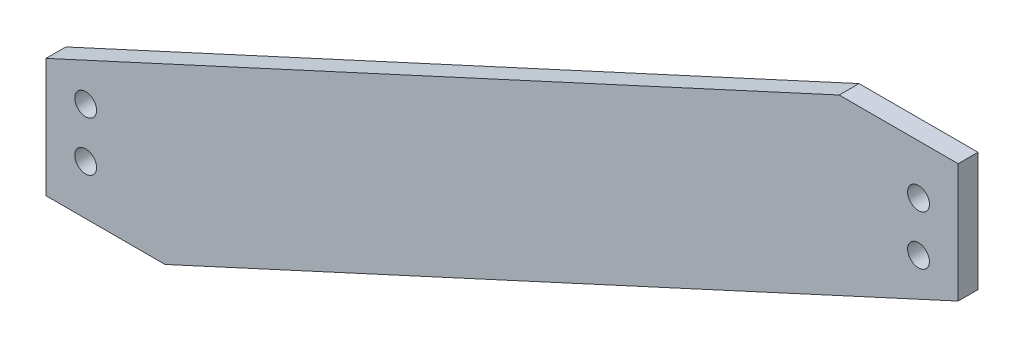
SolidWorks part; units mm, degrees
ref_plane "Front" through (0, 0, 0) normal (0, 0, 1) x (1, 0, 0)
ref_plane "Top" through (0, 0, 0) normal (0, 1, 0) x (1, 0, 0)
ref_plane "Right" through (0, 0, 0) normal (1, 0, 0) x (0, 0, -1)
sketch "Sketch1" plane through (0, 0, 0) normal (0, 0, 1) x (1, 0, 0)
  line L0 (0, 0) -> (20, 0)
  line L1 (20, 0) -> (230, 122)
  line L2 (230, 122) -> (210, 122)
  line L3 (210, 122) -> (0, 0)
  dimension "D1" = 20
  dimension "D2" = 122
  dimension "D3" = 230
extrude "Boss-Extrude1" add sketch "Sketch1" along normal blind 5
sketch "Sketch2" plane through (0, 0, 5) normal (0, 0, 1) x (1, 0, 0)
  line L0 (0, 0) -> (0, 30)
  line L1 (0, 30) -> (200, 122)
  line L2 (200, 122) -> (210, 122)
  line L3 (210, 122) -> (230, 122)
  line L4 (230, 122) -> (230, 92)
  line L5 (230, 92) -> (30, 0)
  line L6 (30, 0) -> (0, 0)
  dimension "D1" = 30
  dimension "D2" = 30
  dimension "D3" = 30
extrude "Boss-Extrude2" add sketch "Sketch2" against normal up to surface (5 mm away) up to face at (115, 61, 0)
hole_wizard "M5 Clearance Hole1" positions "Sketch3" profile "Sketch4" hole size "M5" standard "ISO" end condition through all
sketch "Sketch3" plane through (0, 0, 5) normal (0, 0, 1) x (1, 0, 0)
  line L0 (0, 30) -> (0, 0) construction
  line L1 (0, 0) -> (30, 0) construction
  line L2 (230, 92) -> (230, 122) construction
  line L3 (230, 122) -> (200, 122) construction
  line L4 (10, 25) -> (10, 0) construction
  line L6 (220, 97) -> (220, 122) construction
  point P0 (10, 25)
  point P2 (220, 97)
  point P22 (10, 12.5)
  point P24 (220, 109.5)
  dimension "D1" = 10
  dimension "D2" = 25
  dimension "D3" = 10
  dimension "D4" = 25
sketch "Sketch4" plane through (10, 25, 5) normal (1, 0, 0) x (0, -1, 0)
  line L0 (0, 0) -> (0, 5)
  line L1 (0, 5) -> (2.75, 5)
  line L2 (2.75, 5) -> (2.75, 0)
  line L5 (2.75, 0) -> (0, 0)
  line L11 (0, -6.35) -> (0, 107.95) construction
  dimension "Thru Hole Dia." = 5.5
  dimension "Thru Hole Depth" = 5
